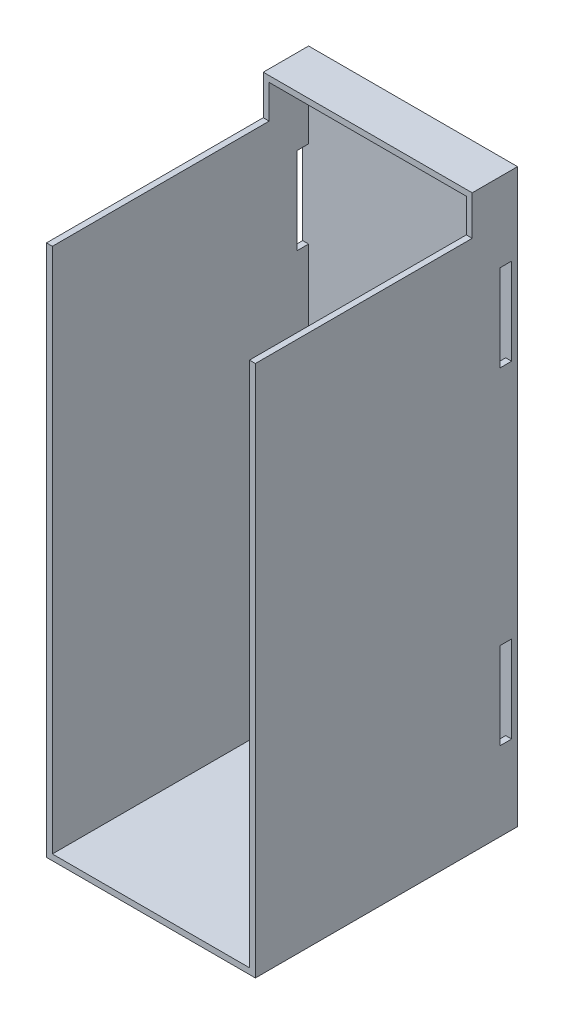
SolidWorks part; units mm, degrees
ref_plane "Спереди" through (0, 0, 0) normal (0, 0, 1) x (1, 0, 0)
ref_plane "Сверху" through (0, 0, 0) normal (0, 1, 0) x (1, 0, 0)
ref_plane "Справа" through (0, 0, 0) normal (1, 0, 0) x (0, 0, -1)
sketch "Эскиз1" plane through (0, 0, 0) normal (0, 0, 1) x (1, 0, 0)
  line L1 (0, 0) -> (53, 0)
  line L2 (0, 0) -> (0, 145)
  line L3 (0, 145) -> (53, 145)
  line L4 (53, 0) -> (53, 145)
  dimension "D1" = 145
  dimension "D2" = 53
extrude "Бобышка-Вытянуть1" add sketch "Эскиз1" along normal blind 1.5
sketch "Эскиз2" plane through (0, 0, 1.5) normal (0, 0, 1) x (1, 0, 0)
  line L0 (1.5, 145) -> (1.5, 1.5)
  line L1 (53, 145) -> (0, 145) construction
  line L2 (51.5, 1.5) -> (51.5, 145)
  line L3 (1.5, 1.5) -> (51.5, 1.5)
  line L4 (0, 0) -> (53, 0) construction
  line L5 (53, 0) -> (53, 145) construction
  line L6 (0, 145) -> (0, 0) construction
  line L7 (1.5, 145) -> (0, 145)
  line L8 (0, 145) -> (0, 0)
  line L9 (0, 0) -> (53, 0)
  line L10 (53, 0) -> (53, 145)
  line L11 (53, 145) -> (51.5, 145)
  dimension "D1" = 1.5
  dimension "D2" = 1.5
  dimension "D3" = 1.5
extrude "Бобышка-Вытянуть2" add sketch "Эскиз2" along normal blind 65
sketch "Эскиз3" plane through (0, 0, 1.5) normal (0, 0, 1) x (1, 0, 0)
  line L0 (1.5, 143.5) -> (51.5, 143.5)
  line L1 (1.5, 1.5) -> (1.5, 145) construction
  line L2 (51.5, 145) -> (51.5, 1.5) construction
  line L3 (51.5, 145) -> (1.5, 145) construction
  line L4 (1.5, 143.5) -> (1.5, 145)
  line L5 (1.5, 145) -> (51.5, 145)
  line L6 (51.5, 145) -> (51.5, 143.5)
  dimension "D1" = 1.5
extrude "Бобышка-Вытянуть3" add sketch "Эскиз3" along normal blind 10
sketch "Эскиз4" plane through (53, 0, 0) normal (1, 0, 0) x (0, 0, -1)
  line L0 (-4.5, 20) -> (-4.5, 0) construction
  line L1 (-4.5, 125) -> (-1.5, 125)
  line L2 (-4.5, 125) -> (-4.5, 103)
  line L3 (-4.5, 103) -> (-1.5, 103)
  line L4 (-1.5, 125) -> (-1.5, 103)
  line L5 (-4.5, 42) -> (-1.5, 42)
  line L6 (-4.5, 42) -> (-4.5, 20)
  line L7 (-4.5, 20) -> (-1.5, 20)
  line L8 (-1.5, 42) -> (-1.5, 20)
  line L9 (-66.5, 0) -> (0, 0) construction
  line L10 (-4.5, 125) -> (-4.5, 145) construction
  line L11 (-66.5, 145) -> (0, 145) construction
  line L12 (0, 0) -> (0, 145) construction
  dimension "D1" = 1.5
  dimension "D2" = 22
  dimension "D3" = 3
  dimension "D4" = 20
extrude "Вырез-Вытянуть1" cut sketch "Эскиз4" against normal blind 100
sketch "Эскиз5" plane through (53, 0, 0) normal (1, 0, 0) x (0, 0, -1)
  line L1 (-66.5, 145) -> (-11.5, 145)
  line L2 (-66.5, 145) -> (-66.5, 135)
  line L3 (-66.5, 135) -> (-11.5, 135)
  line L4 (-11.5, 145) -> (-11.5, 135)
  dimension "D1" = 55
  dimension "D2" = 10
extrude "Вырез-Вытянуть2" cut sketch "Эскиз5" against normal blind 100
